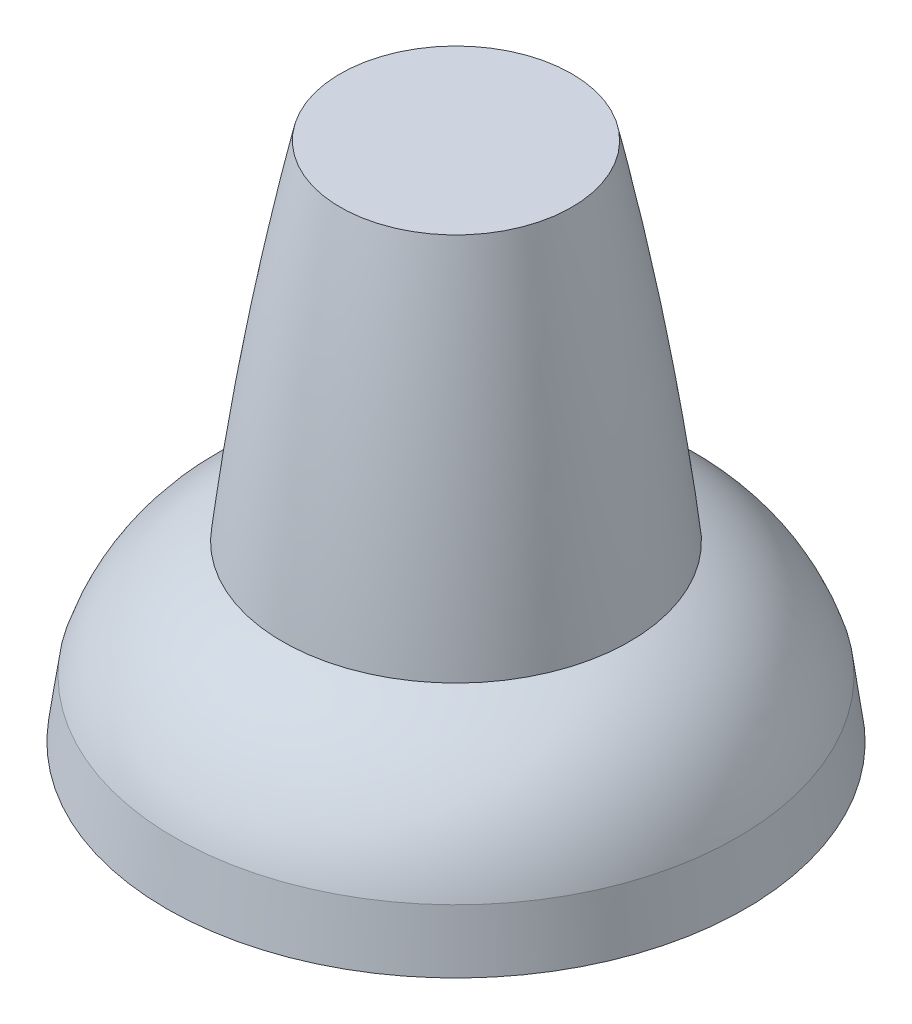
SolidWorks part; units mm, degrees
material "ABS"
ref_plane "Front Plane" through (0, 0, 0) normal (0, 0, 1) x (1, 0, 0)
ref_plane "Top Plane" through (0, 0, 0) normal (0, 1, 0) x (1, 0, 0)
ref_plane "Right Plane" through (0, 0, 0) normal (1, 0, 0) x (0, 0, -1)
sketch "Sketch2" plane through (0, 0, 0) normal (0, 0, 1) x (1, 0, 0)
  line L1 (0, 0) -> (0, 5)
  line L2 (0, 5) -> (0, 15)
  line L3 (0, 15) -> (0, 45)
  line L4 (25, 0) -> (24.3206, 5)
  line L5 (0, 0) -> (25, 0)
  line L9 (0, 45) -> (10, 45)
  spline S0 degree 2 poles (24.3206, 5) (22.0634, 12.1407) (15, 15) knots 0 0 0 1 1 1
  spline S1 degree 2 poles (15, 15) (13.2803, 30.1289) (10, 45) knots 0 0 0 1 1 1
  point P4 (0, 0)
revolve "Revolve1" add sketch "Sketch2" angle 360 about L3
